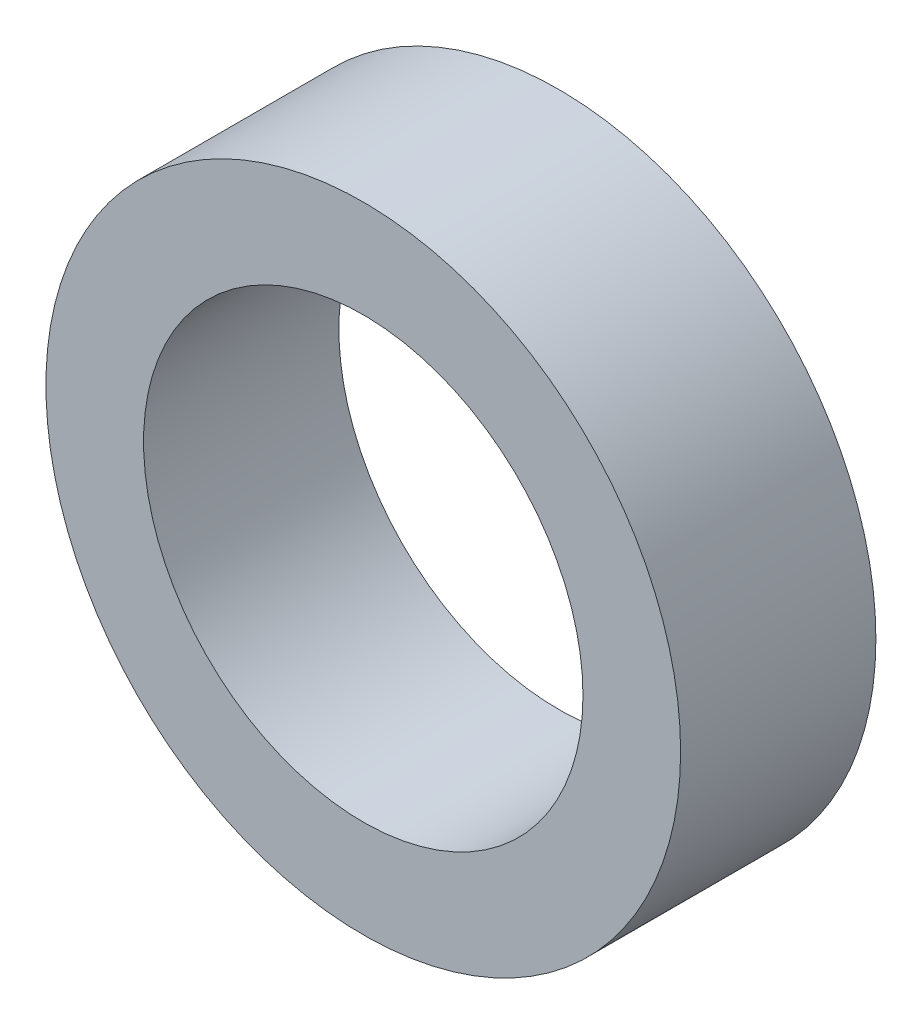
SolidWorks part; units mm, degrees
ref_plane "Front Plane" through (0, 0, 0) normal (0, 0, 1) x (1, 0, 0)
ref_plane "Top Plane" through (0, 0, 0) normal (0, 1, 0) x (1, 0, 0)
ref_plane "Right Plane" through (0, 0, 0) normal (1, 0, 0) x (0, 0, -1)
sketch "Sketch1" plane through (0, 0, 0) normal (0, 0, 1) x (1, 0, 0)
  circle A0 centre (0, 0) radius 4.5
  circle A1 centre (0, 0) radius 6.5
  dimension "D1" = 9
  dimension "D2" = 2
extrude "Boss-Extrude1" add sketch "Sketch1" along normal blind 4
